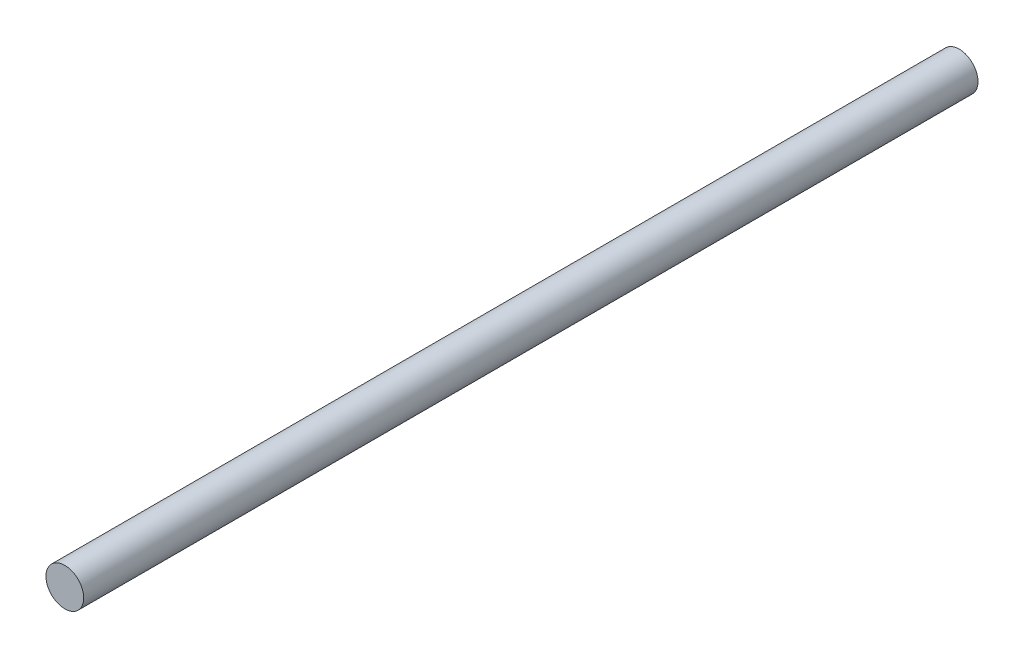
SolidWorks part; units mm, degrees
material "AISI 1020 Steel, Cold Rolled"
ref_plane "Płaszczyzna przednia" through (0, 0, 0) normal (0, 0, 1) x (1, 0, 0)
ref_plane "Płaszczyzna górna" through (0, 0, 0) normal (0, 1, 0) x (1, 0, 0)
ref_plane "Płaszczyzna prawa" through (0, 0, 0) normal (1, 0, 0) x (0, 0, -1)
sketch "Szkic1" plane through (0, 0, 0) normal (0, 0, 1) x (1, 0, 0)
  circle A0 centre (0, 0) radius 5
  dimension "D1" = 10
extrude "Dodanie-wyciągnięcie1" add sketch "Szkic1" along normal blind 237
